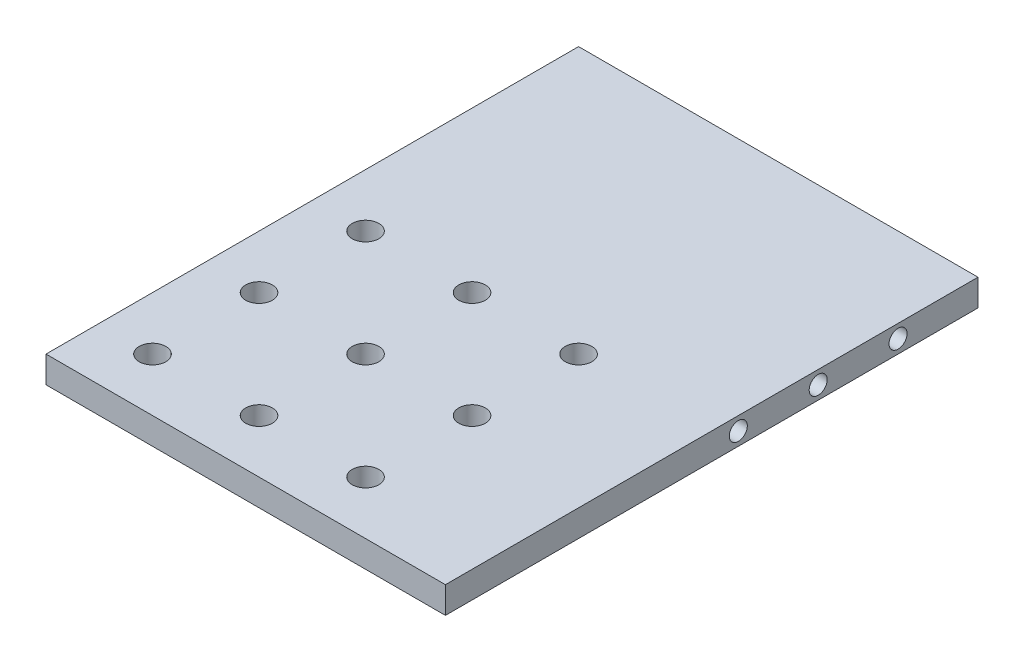
SolidWorks part; units mm, degrees
ref_plane "Front Plane" through (0, 0, 0) normal (0, 0, 1) x (1, 0, 0)
ref_plane "Top Plane" through (0, 0, 0) normal (0, 1, 0) x (1, 0, 0)
ref_plane "Right Plane" through (0, 0, 0) normal (1, 0, 0) x (0, 0, -1)
sketch "Sketch1" plane through (0, 0, 0) normal (0, 1, 0) x (1, 0, 0)
  line L0 (47.625, 63.5) -> (47.625, -63.5)
  line L1 (-47.625, 63.5) -> (47.625, 63.5)
  line L2 (-47.625, 63.5) -> (-47.625, -63.5)
  line L3 (-47.625, -63.5) -> (47.625, -63.5)
  line L5 (-47.625, 63.5) -> (47.625, -63.5) construction
  line L6 (-47.625, -63.5) -> (47.625, 63.5) construction
  circle A0 centre (-34.925, 0) radius 3.175
  circle A1 centre (-9.525, 0) radius 3.175
  circle A2 centre (15.875, 0) radius 3.175
  circle A6 centre (-9.525, -25.4) radius 3.175
  circle A7 centre (15.875, -25.4) radius 3.175
  circle A8 centre (-9.525, -50.8) radius 3.175
  circle A9 centre (15.875, -50.8) radius 3.175
  circle A10 centre (-34.925, -25.4) radius 3.175
  circle A11 centre (-34.925, -50.8) radius 3.175
  point P0 (0, 0)
  point P8 (0, 0)
  dimension "D5" = 6.35
  dimension "D1" = 95.25
  dimension "D2" = 127
  dimension "D3" = 12.7
  dimension "D4" = 12.7
  dimension "D6" = 3
  dimension "D11" = 3
extrude "Boss-Extrude1" add sketch "Sketch1" along normal blind 6.35
sketch "Sketch2" plane through (47.625, 0, 0) normal (1, 0, 0) x (0, 0, -1)
  line L0 (-63.5, 0) -> (63.5, 0) construction
  line L1 (63.5, 6.35) -> (63.5, 0) construction
  circle A0 centre (44.4424, 3.175) radius 2.1527
  circle A1 centre (25.3924, 3.175) radius 2.1527
  circle A2 centre (6.3424, 3.175) radius 2.1527
  dimension "D1" = 4.3053
  dimension "D2" = 3.175
  dimension "D3" = 19.0576
  dimension "D4" = 3
extrude "Cut-Extrude1" cut sketch "Sketch2" against normal blind 25.4
